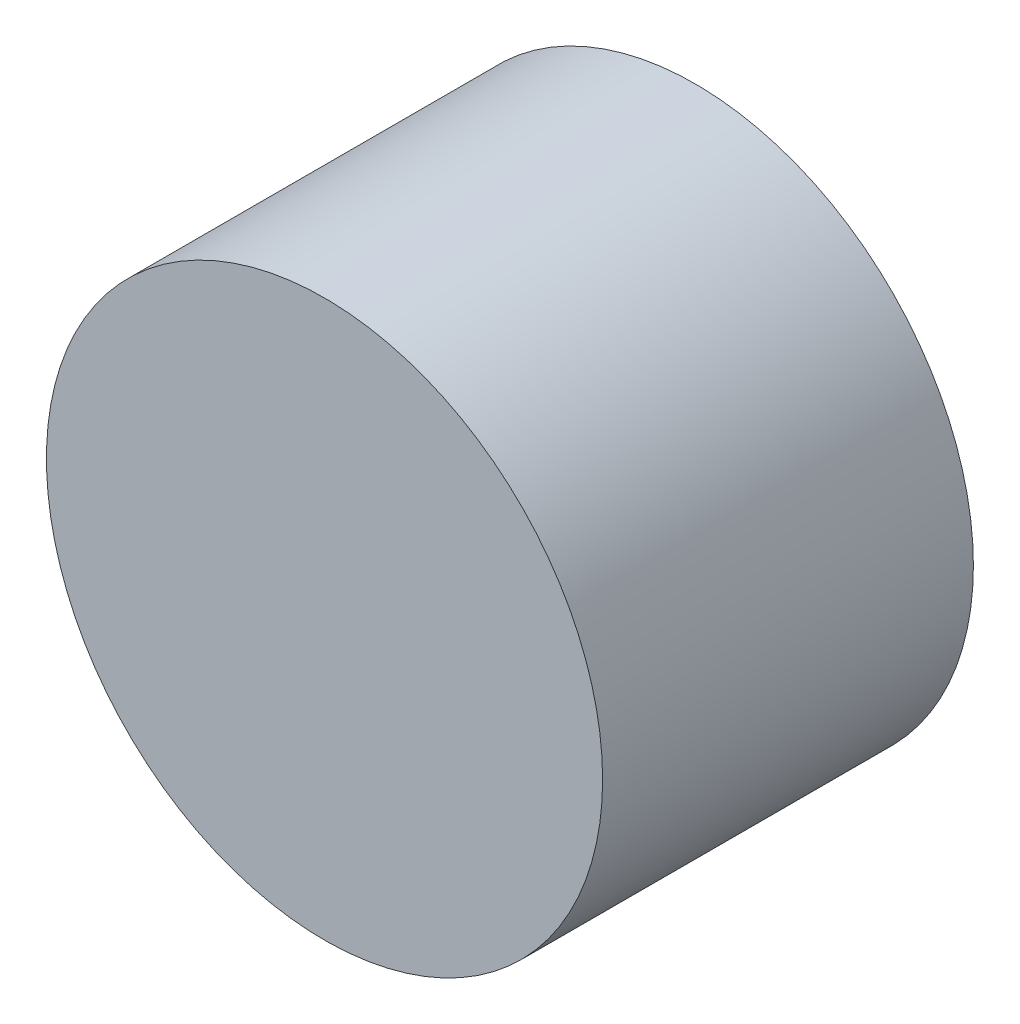
SolidWorks part; units mm, degrees
material "ABS"
ref_plane "Alzado" through (0, 0, 0) normal (0, 0, 1) x (1, 0, 0)
ref_plane "Planta" through (0, 0, 0) normal (0, 1, 0) x (1, 0, 0)
ref_plane "Vista lateral" through (0, 0, 0) normal (1, 0, 0) x (0, 0, -1)
sketch "Croquis1" plane through (0, 0, 0) normal (0, 0, 1) x (1, 0, 0)
  circle A0 centre (0, 0) radius 75
  dimension "D1" = 150
extrude "Saliente-Extruir1" add sketch "Croquis1" along normal blind 100
shell "Vaciado1" thickness 10
